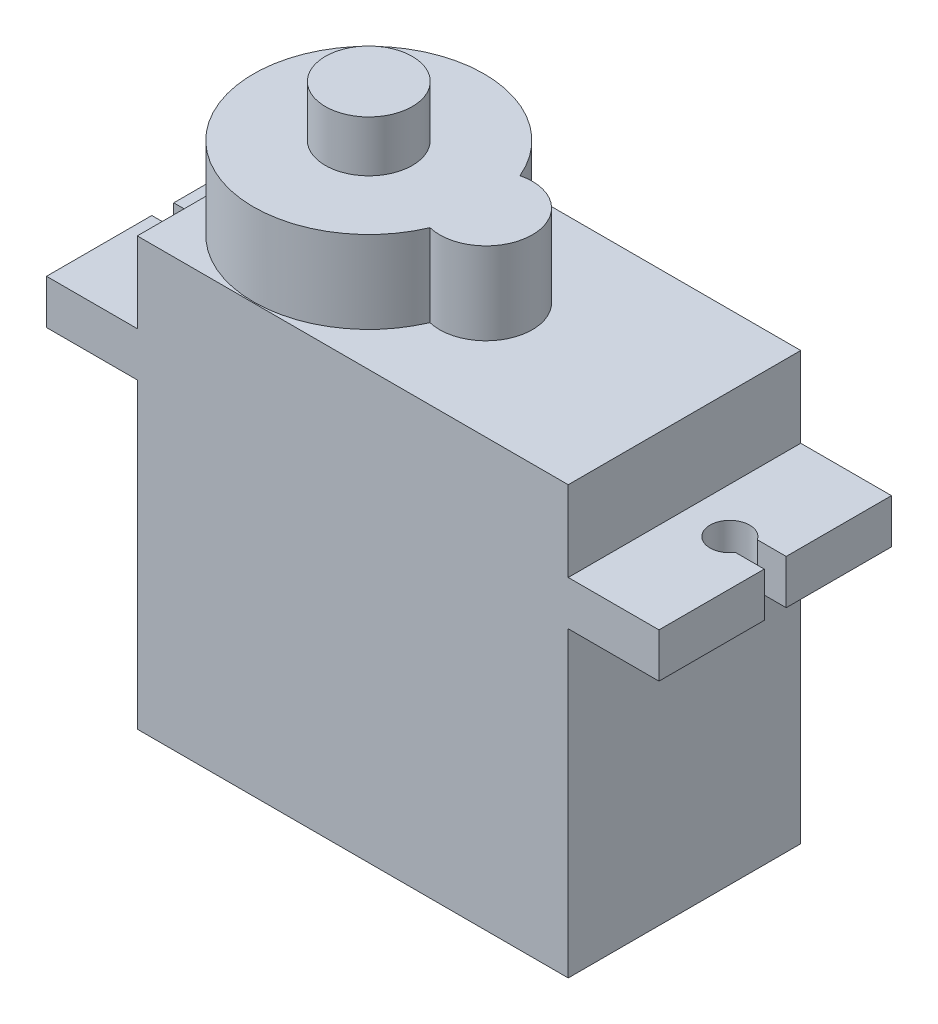
SolidWorks part; units mm, degrees
ref_plane "Plano frontal" through (0, 0, 0) normal (0, 0, 1) x (1, 0, 0)
ref_plane "Plano superior" through (0, 0, 0) normal (0, 1, 0) x (1, 0, 0)
ref_plane "Plano direito" through (0, 0, 0) normal (1, 0, 0) x (0, 0, -1)
sketch "Esboço1" plane through (0, 0, 0) normal (0, 1, 0) x (1, 0, 0)
  line L1 (11.4, 6.15) -> (-11.4, 6.15)
  line L2 (11.4, 6.15) -> (11.4, -6.15)
  line L3 (11.4, -6.15) -> (-11.4, -6.15)
  line L4 (-11.4, 6.15) -> (-11.4, -6.15)
  line L5 (11.4, 6.15) -> (-11.4, -6.15) construction
  line L6 (11.4, -6.15) -> (-11.4, 6.15) construction
  point P0 (0, 0)
  dimension "D1" = 22.8
  dimension "D2" = 12.3
extrude "Ressalto-extrusão1" add sketch "Esboço1" along normal blind 16
sketch "Esboço2" plane through (0, 16, 0) normal (0, 1, 0) x (1, 0, 0)
  line L1 (-16.2, 6.15) -> (16.2, 6.15)
  line L2 (-16.2, 6.15) -> (-16.2, -6.15)
  line L3 (-16.2, -6.15) -> (16.2, -6.15)
  line L4 (16.2, 6.15) -> (16.2, -6.15)
  line L5 (-16.2, 6.15) -> (16.2, -6.15) construction
  line L6 (-16.2, -6.15) -> (16.2, 6.15) construction
  point P0 (0, 0)
  dimension "D1" = 32.4
  dimension "D2" = 12.3
extrude "Ressalto-extrusão2" add sketch "Esboço2" along normal blind 2.35
sketch "Esboço3" plane through (0, 18.35, 0) normal (0, 1, 0) x (-1, 0, 0)
  line L0 (16.2, 6.15) -> (-16.2, 6.15) construction
  line L1 (-11.4, -6.15) -> (11.4, -6.15)
  line L2 (-11.4, -6.15) -> (-11.4, 6.15)
  line L3 (-11.4, 6.15) -> (11.4, 6.15)
  line L4 (11.4, -6.15) -> (11.4, 6.15)
  line L5 (-11.4, -6.15) -> (11.4, 6.15) construction
  line L6 (-11.4, 6.15) -> (11.4, -6.15) construction
  point P0 (0, 0)
  dimension "D1" = 22.8
extrude "Ressalto-extrusão3" add sketch "Esboço3" along normal blind 4.25
sketch "Esboço4" plane through (0, 18.35, 0) normal (0, 1, 0) x (1, 0, 0)
  line L0 (13.8, 6.15) -> (13.8, -6.15) construction
  line L1 (16.2, 6.15) -> (11.4, 6.15) construction
  line L2 (11.4, -6.15) -> (16.2, -6.15) construction
  line L3 (0, 6.15) -> (0, -6.15) construction
  line L4 (16.2, -6.15) -> (16.2, 6.15) construction
  line L5 (16.2, 0) -> (11.4, 0) construction
  line L6 (11.4, -6.15) -> (11.4, 6.15) construction
  line L7 (11.4, 6.15) -> (-11.4, 6.15) construction
  line L8 (-11.4, -6.15) -> (11.4, -6.15) construction
  line L9 (16.2, 0) -> (16.2, 0.58)
  line L10 (16.2, 0.58) -> (14.6753, 0.58)
  line L11 (16.2, -0.58) -> (14.6753, -0.58)
  line L12 (16.2, 0) -> (16.2, -0.58)
  line L13 (-16.2, 0.58) -> (-14.6753, 0.58)
  line L14 (-16.2, 0) -> (-16.2, 0.58)
  line L15 (-16.2, 0) -> (-16.2, -0.58)
  line L16 (-16.2, -0.58) -> (-14.6753, -0.58)
  arc A0 (14.6753, 0.58) -> (14.6753, -0.58) centre (13.8, 0) ccw
  arc A1 (-14.6753, 0.58) -> (-14.6753, -0.58) centre (-13.8, 0) cw
  dimension "D1" = 2.1
  dimension "D2" = 1.16
extrude "Corte-extrusão1" cut sketch "Esboço4" against normal blind 4.25
sketch "Esboço5" plane through (0, 22.6, 0) normal (0, 1, 0) x (1, 0, 0)
  line L0 (-11.4, 0) -> (11.4, 0) construction
  line L1 (-11.4, 6.15) -> (-11.4, -6.15) construction
  line L2 (11.4, -6.15) -> (11.4, 6.15) construction
  line L3 (-11.4, 6.15) -> (-5.3, 6.15) construction
  line L4 (11.4, 6.15) -> (-11.4, 6.15) construction
  line L5 (-11.4, 6.15) -> (-11.4, -6.15) construction
  line L6 (-11.4, 6.15) -> (-11.4, 0) construction
  line L7 (-5.3, 6.15) -> (-5.3, 0) construction
  arc A0 (0.316, 2.3814) -> (0.316, -2.3814) centre (-5.3, 0) ccw
  arc A1 (0.316, -2.3814) -> (0.316, 2.3814) centre (0.9, 0) ccw
  dimension "D1" = 6.1
  dimension "D2" = 2.452
  dimension "D3" = 6.2
extrude "Ressalto-extrusão4" add sketch "Esboço5" along normal blind 4.35
sketch "Esboço6" plane through (0, 26.95, 0) normal (0, 1, 0) x (1, 0, 0)
  circle A0 centre (-5.3, 0) radius 2.3
  dimension "D1" = 4.6
extrude "Ressalto-extrusão5" add sketch "Esboço6" along normal blind 2.7
